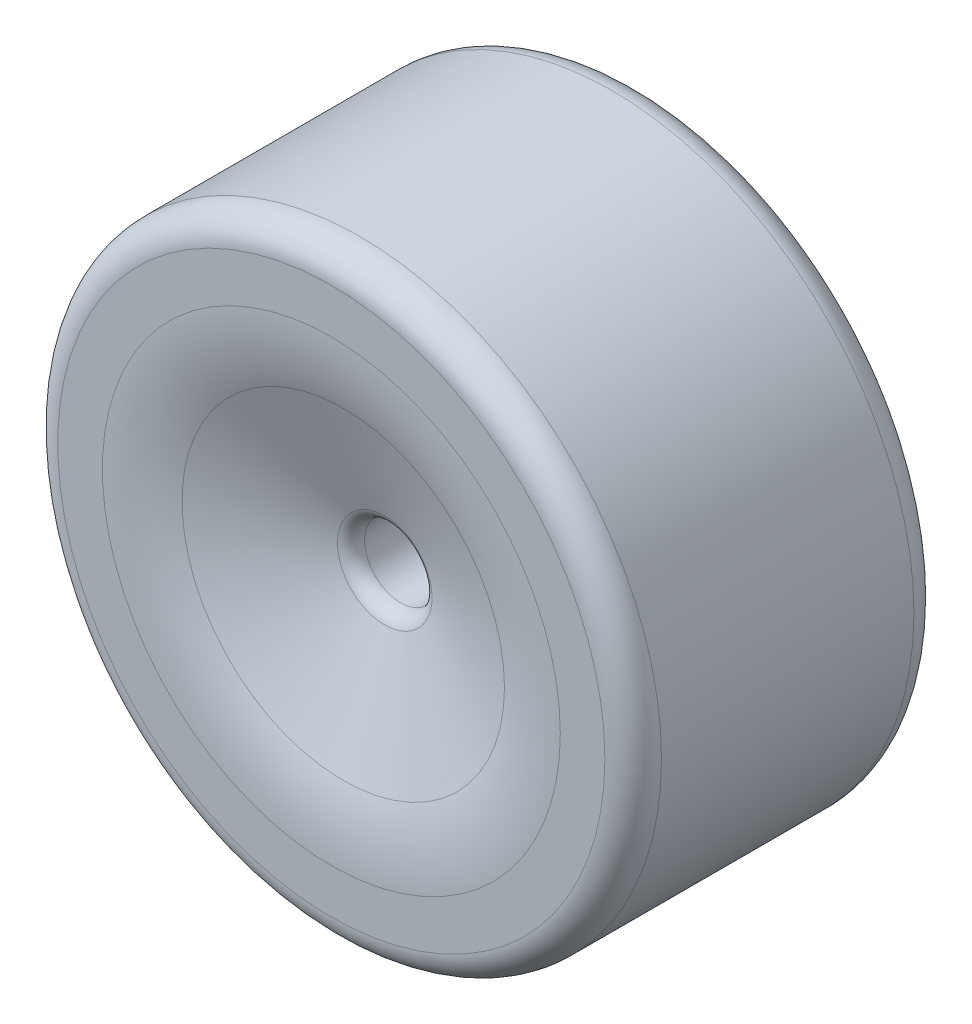
SolidWorks part; units mm, degrees
ref_plane "Front" through (0, 0, 0) normal (0, 0, 1) x (1, 0, 0)
ref_plane "Top" through (0, 0, 0) normal (0, 1, 0) x (1, 0, 0)
ref_plane "Right" through (0, 0, 0) normal (1, 0, 0) x (0, 0, -1)
sketch "Sketch1" plane through (0, 0, 0) normal (0, 0, 1) x (1, 0, 0)
  circle A0 centre (0, 0) radius 53.34
  dimension "D1" = 106.68
extrude "Extrude1" add sketch "Sketch1" along normal blind 54.61
fillet "Fillet1" radius 5 2 edges at (53.34, 0, 0) (53.34, 0, 54.61)
sketch "Sketch2" plane through (0, 0, 0) normal (0, 0, -1) x (-1, 0, 0)
  circle A0 centre (0, 0) radius 27.432
  dimension "D1" = 54.864
extrude "Cut-Extrude1" cut sketch "Sketch2" against normal blind 17.78
fillet "Fillet2" radius 2 1 edges at (-27.432, 0, 0)
sketch "Sketch3" plane through (0, 0, 54.61) normal (0, 0, 1) x (1, 0, 0)
  circle A0 centre (0, 0) radius 34.29
  dimension "D1" = 68.58
extrude "Cut-Extrude2" cut sketch "Sketch3" against normal blind 10.16 draft 70
fillet "Fillet3" radius 35 1 edges at (34.29, 0, 54.61)
sketch "Sketch4" plane through (0, 0, 44.45) normal (0, 0, 1) x (1, 0, 0)
  circle A1 centre (0, 0) radius 6.3756
  circle A2 centre (0, 0) radius 6.3756
  dimension "D1" = 0
extrude "Cut-Extrude3" cut sketch "Sketch4" against normal blind 15.24
fillet "Fillet4" radius 3 1 edges at (6.3756, 0, 44.45)
